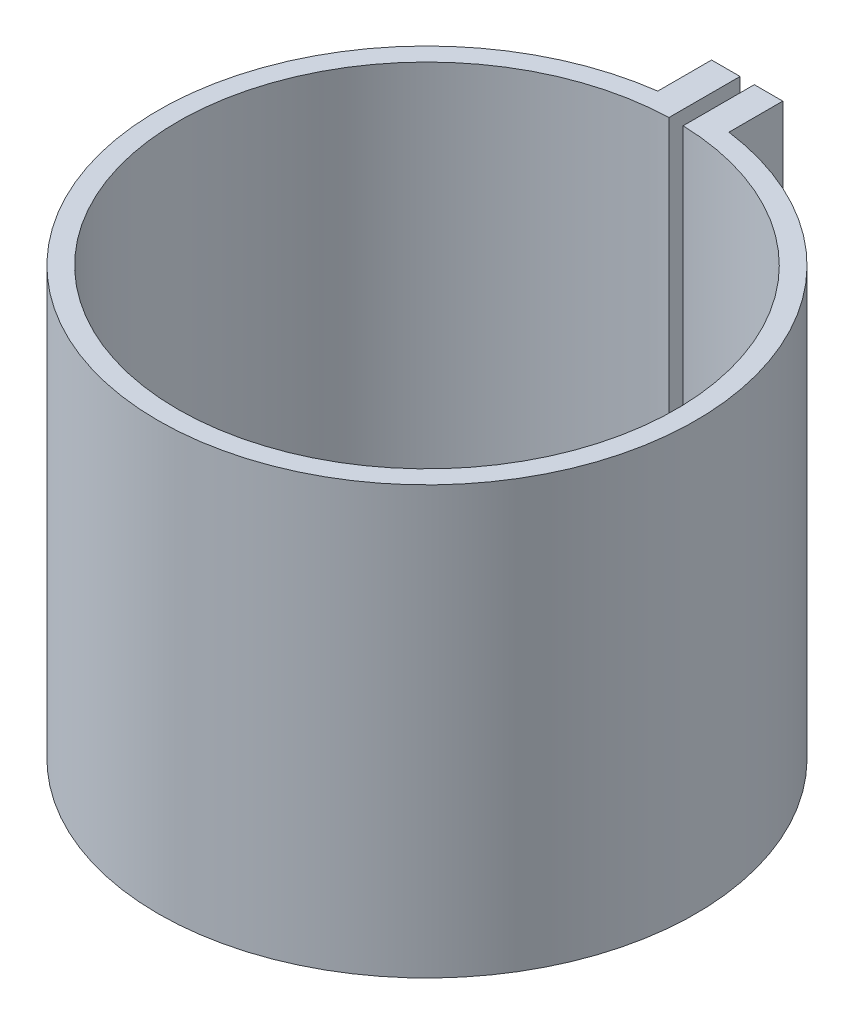
SolidWorks part; units mm, degrees
ref_plane "Front" through (0, 0, 0) normal (0, 0, 1) x (1, 0, 0)
ref_plane "Top" through (0, 0, 0) normal (0, 1, 0) x (1, 0, 0)
ref_plane "Right" through (0, 0, 0) normal (1, 0, 0) x (0, 0, -1)
sketch "Sketch1" plane through (0, 0, 0) normal (0, 1, 0) x (1, 0, 0)
  line L0 (-2.5, 22.4929) -> (-2.5, 18.712)
  line L1 (0, 0) -> (0, 10.8393) construction
  line L2 (-0.5, 22.4929) -> (-0.5, 17.4929)
  line L3 (-2.5, 22.4929) -> (-0.5, 22.4929)
  line L4 (2.5, 22.4929) -> (0.5, 22.4929)
  line L5 (0.5, 22.4929) -> (0.5, 17.4929)
  line L6 (2.5, 22.4929) -> (2.5, 18.712)
  arc A0 (-0.5, 17.4929) -> (0.5, 17.4929) centre (0, 0) ccw
  arc A1 (-2.5, 18.712) -> (2.5, 18.712) centre (0, 0) ccw
  dimension "D3" = 17.5
  dimension "D4" = 1.3783
  dimension "D1" = 1
  dimension "D2" = 2
  dimension "D5" = 5
extrude "Boss-Extrude1" add sketch "Sketch1" along normal mid plane 30
